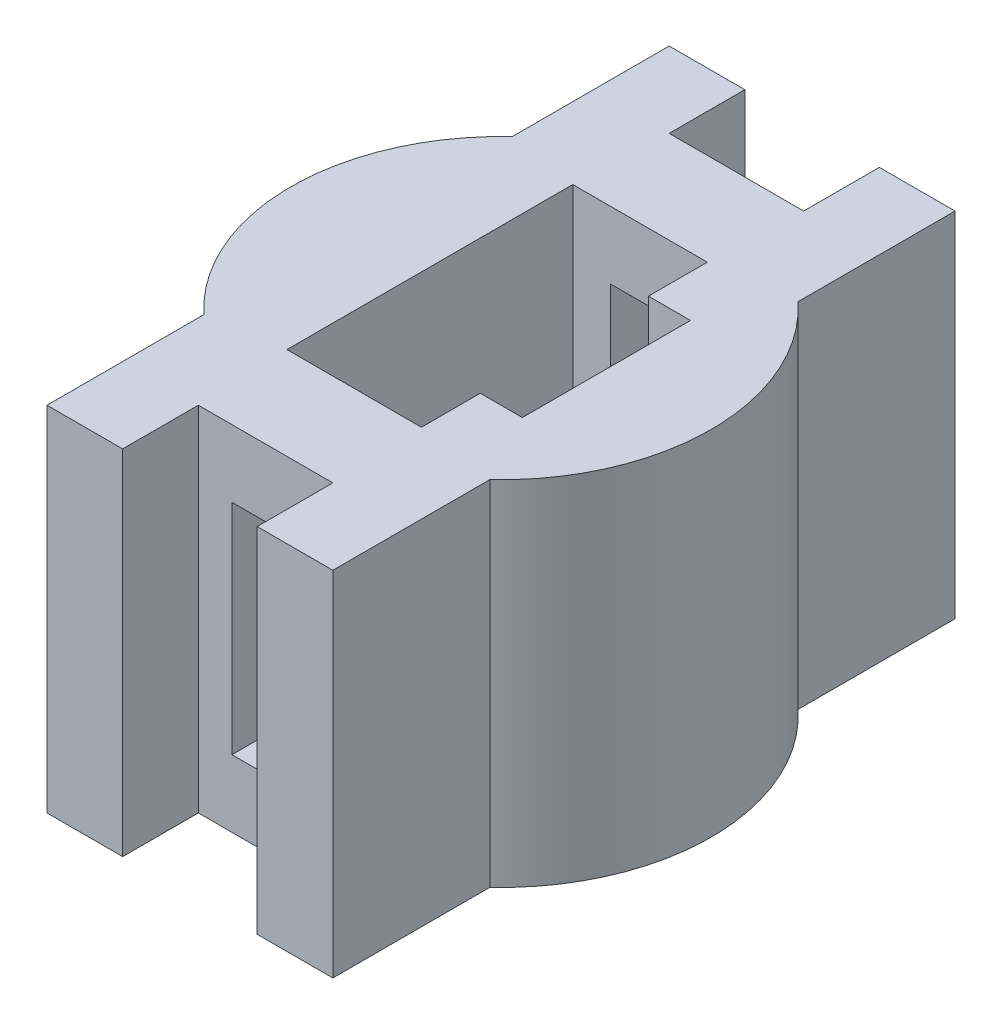
SolidWorks part; units mm, degrees
ref_plane "Front Plane" through (0, 0, 0) normal (0, 0, 1) x (1, 0, 0)
ref_plane "Top Plane" through (0, 0, 0) normal (0, 1, 0) x (1, 0, 0)
ref_plane "Right Plane" through (0, 0, 0) normal (1, 0, 0) x (0, 0, -1)
sketch "Sketch1" plane through (0, 0, 0) normal (0, 0, 1) x (1, 0, 0)
  line L1 (0, 0) -> (34, 0)
  line L2 (0, 0) -> (0, 42)
  line L3 (0, 42) -> (34, 42)
  line L4 (34, 0) -> (34, 42)
  dimension "D1" = 34
  dimension "D2" = 42
extrude "Boss-Extrude1" add sketch "Sketch1" along normal mid plane 74
sketch "Sketch2" plane through (0, 0, 37) normal (0, 0, 1) x (1, 0, 0)
  line L0 (17, 42) -> (9, 42)
  line L1 (34, 42) -> (0, 42) construction
  line L2 (9, 42) -> (9, 0)
  line L3 (0, 0) -> (34, 0) construction
  line L4 (9, 0) -> (17, 0)
  line L5 (17, 0) -> (25, 0)
  line L6 (25, 0) -> (25, 42)
  line L7 (25, 42) -> (17, 42)
  dimension "D1" = 8
  dimension "D2" = 8
extrude "Cut-Extrude1" cut sketch "Sketch2" against normal blind 9
sketch "Sketch3" plane through (0, 0, -37) normal (0, 0, -1) x (-1, 0, 0)
  line L0 (-17, 42) -> (-25, 42)
  line L1 (-34, 42) -> (0, 42) construction
  line L2 (-25, 42) -> (-25, 0)
  line L3 (-25, 0) -> (-17, 0)
  line L4 (0, 0) -> (-34, 0) construction
  line L5 (-17, 0) -> (-9, 0)
  line L6 (-9, 0) -> (-9, 42)
  line L7 (-9, 42) -> (-17, 42)
  dimension "D1" = 9
extrude "Cut-Extrude2" cut sketch "Sketch3" against normal blind 9
sketch "Sketch9" plane through (0, 0, 0) normal (0, 1, 0) x (1, 0, 0)
  circle A0 centre (17, 0) radius 25
  dimension "D1" = 50
  dimension "D2" = 17
extrude "Boss-Extrude3" add sketch "Sketch9" along normal through all
sketch "Sketch10" plane through (0, 42, 0) normal (0, 1, 0) x (1, 0, 0)
  line L0 (25, -28) -> (9, -28) construction
  line L1 (24.5378, -17) -> (8.5378, -17)
  line L2 (24.5378, -17) -> (24.5378, 17)
  line L3 (24.5378, 17) -> (8.5378, 17)
  line L4 (8.5378, -17) -> (8.5378, 17)
  line L5 (9, 28) -> (25, 28) construction
  arc A0 (0, 18.3303) -> (0, -18.3303) centre (17, 0) ccw construction
  point P7 (8.5378, 0)
  dimension "D4" = 8.4622
  dimension "D1" = 16
  dimension "D2" = 34
  dimension "D3" = 11
extrude "Cut-Extrude5" cut sketch "Sketch10" against normal through all
sketch "Sketch11" plane through (24.5378, 0, 0) normal (-1, 0, 0) x (0, 0, 1)
  line L0 (0, 42) -> (-10, 42)
  line L1 (18.3303, 42) -> (-18.3303, 42) construction
  line L2 (-10, 42) -> (-10, 32)
  line L3 (-10, 32) -> (10, 32)
  line L5 (10, 32) -> (10, 42)
  line L6 (10, 42) -> (0, 42)
  point P4 (0, 0)
  point P9 (10.6059, 32)
  dimension "D1" = 10
  dimension "D2" = 10
  dimension "D3" = 10
extrude "Cut-Extrude6" cut sketch "Sketch11" against normal blind 5
sketch "Sketch13" plane through (0, 0, -28) normal (0, 0, -1) x (-1, 0, 0)
  line L0 (-21, 34) -> (-13, 34)
  line L1 (-13, 34) -> (-13, 8)
  line L2 (-13, 8) -> (-21, 8)
  line L3 (-21, 8) -> (-21, 34)
  line L4 (-9, 0) -> (-9, 42) construction
  line L5 (-25, 42) -> (-25, 0) construction
  line L6 (-9, 42) -> (-25, 42) construction
  dimension "D1" = 26
  dimension "D2" = 4
  dimension "D3" = 4
  dimension "D4" = 8
extrude "Cut-Extrude7" cut sketch "Sketch13" against normal through all
